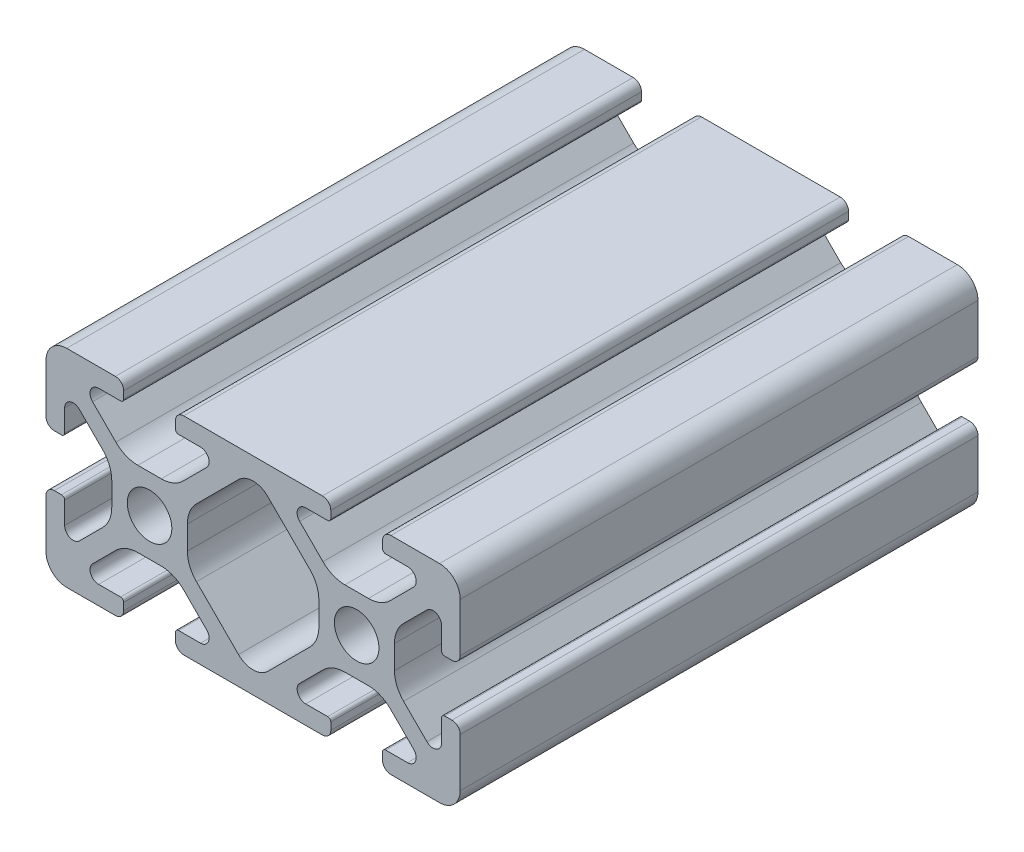
SolidWorks part; units mm, degrees
ref_plane "Plan de face" through (0, 0, 0) normal (0, 0, 1) x (1, 0, 0)
ref_plane "Plan de dessus" through (0, 0, 0) normal (0, 1, 0) x (1, 0, 0)
ref_plane "Plan de droite" through (0, 0, 0) normal (1, 0, 0) x (0, 0, -1)
ref_plane "Plan1" through (0, 0, 0) normal (0, 0, -1) x (-1, 0, 0)
sketch "Esquisse1" plane through (0, 0, 0) normal (0, 0, -1) x (-1, 0, 0)
  line L0 (-40, 6.7) -> (-40, 2)
  line L1 (-38, 0) -> (-33.3, 0)
  line L2 (-32.5, 0.8) -> (-32.5, 1.5)
  line L3 (-32.8, 1.8) -> (-34.9184, 1.8)
  line L4 (-35.5064, 3.2196) -> (-33.2547, 5.4713)
  line L5 (-31.1334, 6.35) -> (-28.8666, 6.35)
  line L6 (-26.7453, 5.4713) -> (-24.4936, 3.2196)
  line L7 (-25.0816, 1.8) -> (-27.2, 1.8)
  line L8 (-27.5, 1.5) -> (-27.5, 0.8)
  line L9 (-26.7, 0) -> (-13.3, 0)
  line L10 (-12.5, 0.8) -> (-12.5, 1.5)
  line L11 (-12.8, 1.8) -> (-14.9184, 1.8)
  line L12 (-15.5064, 3.2196) -> (-13.2547, 5.4713)
  line L13 (-11.1334, 6.35) -> (-8.8666, 6.35)
  line L14 (-6.7453, 5.4713) -> (-4.4936, 3.2196)
  line L15 (-5.0816, 1.8) -> (-7.2, 1.8)
  line L16 (-7.5, 1.5) -> (-7.5, 0.8)
  line L17 (-6.7, 0) -> (-2, 0)
  line L18 (0, 2) -> (0, 6.7)
  line L19 (-0.8, 7.5) -> (-1.5, 7.5)
  line L20 (-1.8, 7.2) -> (-1.8, 5.0816)
  line L21 (-3.2196, 4.4936) -> (-5.4713, 6.7453)
  line L22 (-6.35, 8.8666) -> (-6.35, 11.1334)
  line L23 (-5.4713, 13.2547) -> (-3.2196, 15.5064)
  line L24 (-1.8, 14.9184) -> (-1.8, 12.8)
  line L25 (-1.5, 12.5) -> (-0.8, 12.5)
  line L26 (0, 13.3) -> (0, 18)
  line L27 (-2, 20) -> (-6.7, 20)
  line L28 (-7.5, 19.2) -> (-7.5, 18.5)
  line L29 (-7.2, 18.2) -> (-5.0816, 18.2)
  line L30 (-4.4936, 16.7804) -> (-6.7453, 14.5287)
  line L31 (-8.8666, 13.65) -> (-11.1334, 13.65)
  line L32 (-13.2547, 14.5287) -> (-15.5064, 16.7804)
  line L33 (-14.9184, 18.2) -> (-12.8, 18.2)
  line L34 (-12.5, 18.5) -> (-12.5, 19.2)
  line L35 (-13.3, 20) -> (-26.7, 20)
  line L36 (-27.5, 19.2) -> (-27.5, 18.5)
  line L37 (-27.2, 18.2) -> (-25.0816, 18.2)
  line L38 (-24.4936, 16.7804) -> (-26.7453, 14.5287)
  line L39 (-28.8666, 13.65) -> (-31.1334, 13.65)
  line L40 (-33.2547, 14.5287) -> (-35.5064, 16.7804)
  line L41 (-34.9184, 18.2) -> (-32.8, 18.2)
  line L42 (-32.5, 18.5) -> (-32.5, 19.2)
  line L43 (-33.3, 20) -> (-38, 20)
  line L44 (-40, 18) -> (-40, 13.3)
  line L45 (-39.2, 12.5) -> (-38.5, 12.5)
  line L46 (-38.2, 12.8) -> (-38.2, 14.9184)
  line L47 (-36.7804, 15.5064) -> (-34.5287, 13.2547)
  line L48 (-33.65, 11.1334) -> (-33.65, 8.8666)
  line L49 (-34.5287, 6.7453) -> (-36.7804, 4.4936)
  line L50 (-38.2, 5.0816) -> (-38.2, 7.2)
  line L51 (-38.5, 7.5) -> (-39.2, 7.5)
  line L52 (-18.5858, 17.313) -> (-14.5287, 13.2559)
  line L53 (-13.65, 11.1346) -> (-13.65, 8.8654)
  line L54 (-14.5287, 6.7441) -> (-18.5858, 2.687)
  line L55 (-21.4142, 2.687) -> (-25.4713, 6.7441)
  line L56 (-26.35, 8.8654) -> (-26.35, 11.1346)
  line L57 (-25.4713, 13.2559) -> (-21.4142, 17.313)
  arc A0 (-39.2, 7.5) -> (-40, 6.7) centre (-39.2, 6.7) ccw
  arc A1 (-40, 2) -> (-38, 0) centre (-38, 2) ccw
  arc A2 (-33.3, 0) -> (-32.5, 0.8) centre (-33.3, 0.8) ccw
  arc A3 (-32.5, 1.5) -> (-32.8, 1.8) centre (-32.8, 1.5) ccw
  arc A4 (-34.9184, 1.8) -> (-35.5064, 3.2196) centre (-34.9184, 2.6316) cw
  arc A5 (-33.2547, 5.4713) -> (-31.1334, 6.35) centre (-31.1334, 3.35) cw
  arc A6 (-28.8666, 6.35) -> (-26.7453, 5.4713) centre (-28.8666, 3.35) cw
  arc A7 (-24.4936, 3.2196) -> (-25.0816, 1.8) centre (-25.0816, 2.6316) cw
  arc A8 (-27.2, 1.8) -> (-27.5, 1.5) centre (-27.2, 1.5) ccw
  arc A9 (-27.5, 0.8) -> (-26.7, 0) centre (-26.7, 0.8) ccw
  arc A10 (-13.3, 0) -> (-12.5, 0.8) centre (-13.3, 0.8) ccw
  arc A11 (-12.5, 1.5) -> (-12.8, 1.8) centre (-12.8, 1.5) ccw
  arc A12 (-14.9184, 1.8) -> (-15.5064, 3.2196) centre (-14.9184, 2.6316) cw
  arc A13 (-13.2547, 5.4713) -> (-11.1334, 6.35) centre (-11.1334, 3.35) cw
  arc A14 (-8.8666, 6.35) -> (-6.7453, 5.4713) centre (-8.8666, 3.35) cw
  arc A15 (-4.4936, 3.2196) -> (-5.0816, 1.8) centre (-5.0816, 2.6316) cw
  arc A16 (-7.2, 1.8) -> (-7.5, 1.5) centre (-7.2, 1.5) ccw
  arc A17 (-7.5, 0.8) -> (-6.7, 0) centre (-6.7, 0.8) ccw
  arc A18 (-2, 0) -> (0, 2) centre (-2, 2) ccw
  arc A19 (0, 6.7) -> (-0.8, 7.5) centre (-0.8, 6.7) ccw
  arc A20 (-1.5, 7.5) -> (-1.8, 7.2) centre (-1.5, 7.2) ccw
  arc A21 (-1.8, 5.0816) -> (-3.2196, 4.4936) centre (-2.6316, 5.0816) cw
  arc A22 (-5.4713, 6.7453) -> (-6.35, 8.8666) centre (-3.35, 8.8666) cw
  arc A23 (-6.35, 11.1334) -> (-5.4713, 13.2547) centre (-3.35, 11.1334) cw
  arc A24 (-3.2196, 15.5064) -> (-1.8, 14.9184) centre (-2.6316, 14.9184) cw
  arc A25 (-1.8, 12.8) -> (-1.5, 12.5) centre (-1.5, 12.8) ccw
  arc A26 (-0.8, 12.5) -> (0, 13.3) centre (-0.8, 13.3) ccw
  arc A27 (0, 18) -> (-2, 20) centre (-2, 18) ccw
  arc A28 (-6.7, 20) -> (-7.5, 19.2) centre (-6.7, 19.2) ccw
  arc A29 (-7.5, 18.5) -> (-7.2, 18.2) centre (-7.2, 18.5) ccw
  arc A30 (-5.0816, 18.2) -> (-4.4936, 16.7804) centre (-5.0816, 17.3684) cw
  arc A31 (-6.7453, 14.5287) -> (-8.8666, 13.65) centre (-8.8666, 16.65) cw
  arc A32 (-11.1334, 13.65) -> (-13.2547, 14.5287) centre (-11.1334, 16.65) cw
  arc A33 (-15.5064, 16.7804) -> (-14.9184, 18.2) centre (-14.9184, 17.3684) cw
  arc A34 (-12.8, 18.2) -> (-12.5, 18.5) centre (-12.8, 18.5) ccw
  arc A35 (-12.5, 19.2) -> (-13.3, 20) centre (-13.3, 19.2) ccw
  arc A36 (-26.7, 20) -> (-27.5, 19.2) centre (-26.7, 19.2) ccw
  arc A37 (-27.5, 18.5) -> (-27.2, 18.2) centre (-27.2, 18.5) ccw
  arc A38 (-25.0816, 18.2) -> (-24.4936, 16.7804) centre (-25.0816, 17.3684) cw
  arc A39 (-26.7453, 14.5287) -> (-28.8666, 13.65) centre (-28.8666, 16.65) cw
  arc A40 (-31.1334, 13.65) -> (-33.2547, 14.5287) centre (-31.1334, 16.65) cw
  arc A41 (-35.5064, 16.7804) -> (-34.9184, 18.2) centre (-34.9184, 17.3684) cw
  arc A42 (-32.8, 18.2) -> (-32.5, 18.5) centre (-32.8, 18.5) ccw
  arc A43 (-32.5, 19.2) -> (-33.3, 20) centre (-33.3, 19.2) ccw
  arc A44 (-38, 20) -> (-40, 18) centre (-38, 18) ccw
  arc A45 (-40, 13.3) -> (-39.2, 12.5) centre (-39.2, 13.3) ccw
  arc A46 (-38.5, 12.5) -> (-38.2, 12.8) centre (-38.5, 12.8) ccw
  arc A47 (-38.2, 14.9184) -> (-36.7804, 15.5064) centre (-37.3684, 14.9184) cw
  arc A48 (-34.5287, 13.2547) -> (-33.65, 11.1334) centre (-36.65, 11.1334) cw
  arc A49 (-33.65, 8.8666) -> (-34.5287, 6.7453) centre (-36.65, 8.8666) cw
  arc A50 (-36.7804, 4.4936) -> (-38.2, 5.0816) centre (-37.3684, 5.0816) cw
  arc A51 (-38.2, 7.2) -> (-38.5, 7.5) centre (-38.5, 7.2) ccw
  circle A52 centre (-10, 10) radius 2.15
  circle A53 centre (-30, 10) radius 2.15
  arc A54 (-21.4142, 17.313) -> (-18.5858, 17.313) centre (-20, 15.8988) cw
  arc A55 (-14.5287, 13.2559) -> (-13.65, 11.1346) centre (-16.65, 11.1346) cw
  arc A56 (-13.65, 8.8654) -> (-14.5287, 6.7441) centre (-16.65, 8.8654) cw
  arc A57 (-18.5858, 2.687) -> (-21.4142, 2.687) centre (-20, 4.1012) cw
  arc A58 (-25.4713, 6.7441) -> (-26.35, 8.8654) centre (-23.35, 8.8654) cw
  arc A59 (-26.35, 11.1346) -> (-25.4713, 13.2559) centre (-23.35, 11.1346) cw
extrude "Boss.-Extru.1" add sketch "Esquisse1" against normal blind 50
